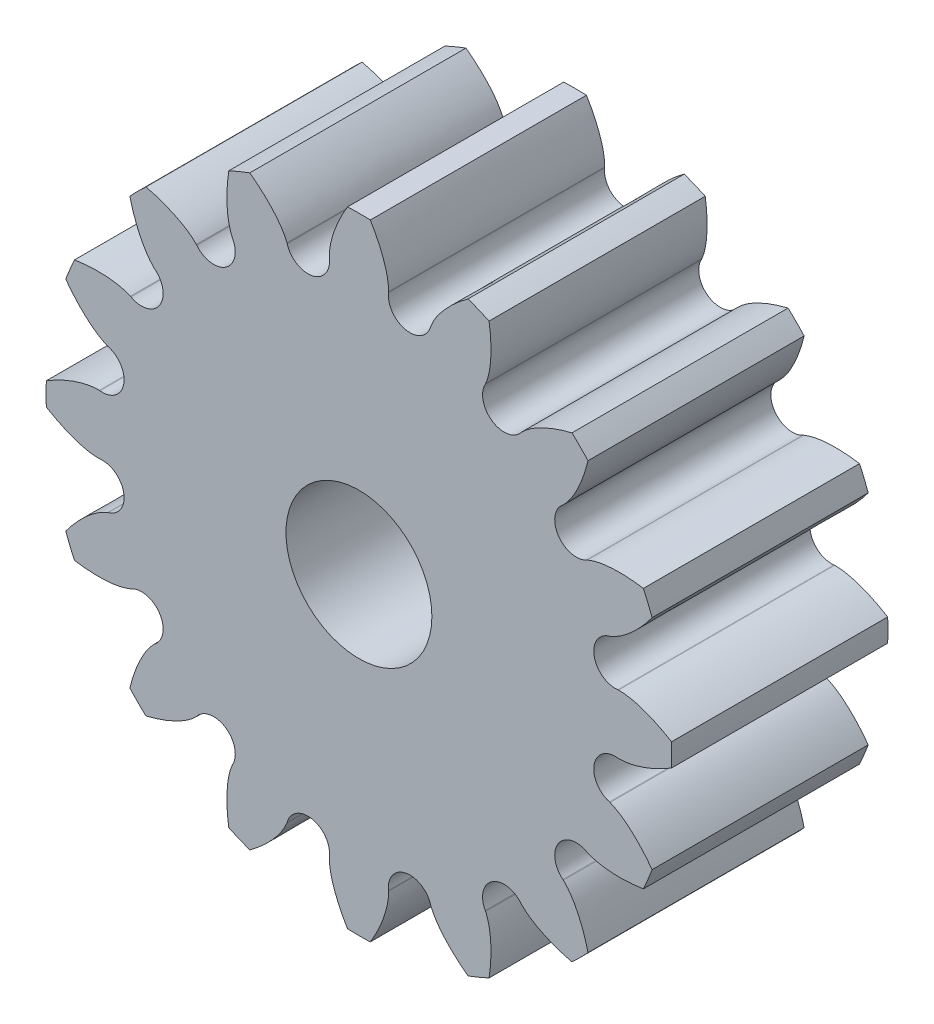
SolidWorks part; units mm, degrees
material "PE Low/Medium Density"
ref_plane "Front Plane" through (0, 0, 0) normal (0, 0, 1) x (1, 0, 0)
ref_plane "Top Plane" through (0, 0, 0) normal (0, 1, 0) x (1, 0, 0)
ref_plane "Right Plane" through (0, 0, 0) normal (1, 0, 0) x (0, 0, -1)
sketch "Involute construction sketch" plane through (0, 0, 0) normal (0, 0, 1) x (1, 0, 0)
  line L0 (0, 0) -> (-1.7946, 3.1652) construction
  line L1 (0, 0) -> (-1.096, 3.4696) construction
  line L2 (0, 0) -> (-0.3494, 3.6218) construction
  line L3 (0, 0) -> (0.4126, 3.6151) construction
  line L4 (-2.9284, 2.1595) -> (-2.4145, 2.722) construction
  line L5 (-2.4145, 2.722) -> (-1.7946, 3.1652) construction
  line L6 (-1.7946, 3.1652) -> (-1.096, 3.4696) construction
  line L7 (0, 0) -> (-2.4145, 2.722) construction
  line L8 (0, 0) -> (-2.9284, 2.1595) construction
  line L9 (-1.096, 3.4696) -> (-0.3494, 3.6218) construction
  line L10 (-0.3494, 3.6218) -> (0.4126, 3.6151) construction
  line L11 (-2.9284, 2.1595) -> (-0.6672, 5.2259) construction
  line L12 (-2.4145, 2.722) -> (-0.1342, 4.7446) construction
  line L13 (-1.7946, 3.1652) -> (0.194, 4.2927) construction
  line L14 (-1.096, 3.4696) -> (0.3572, 3.9286) construction
  line L15 (-0.3494, 3.6218) -> (0.4091, 3.6949) construction
  line L17 (0, 0) -> (0, 5.7859) construction
  line L18 (0, 0) -> (0.3795, 3.8534) construction
  line L19 (0, 0) -> (0.6516, 3.2759) construction
  circle A0 centre (0, 0) radius 3.3401 construction
  circle A1 centre (0, 0) radius 3.6386 construction
  circle A2 centre (0, 0) radius 3.8721 construction
  circle A3 centre (0, 0) radius 4.3561 construction
  spline S0 degree 3 poles (0.4126, 3.6151) (0.4138, 3.7219) (0.3608, 3.9584) (0.0805, 4.5656) (-0.328, 4.974) (-0.6672, 5.2259) knots 0 0 0 0 0.160058 0.360049 1 1 1 1 construction
  point P17 (0.1584, 4.3532)
  dimension "D1" = 6.6802
  dimension "D2" = 7.2771
  dimension "D3" = 7.7442
  dimension "D4" = 8.7122
  dimension "D5" = 0.762
  dimension "D6" = 1.524
  dimension "D7" = 2.286
  dimension "D8" = 3.048
  dimension "D9" = 3.81
  dimension "D10" = 5.625
  dimension "D11" = 11.25
sketch "Sketch2" plane through (0, 0, 0) normal (0, 0, 1) x (1, 0, 0)
  line L0 (0, 4.3561) -> (0, 3.3401)
  line L1 (0, 0) -> (0, 5.7859) construction
  line L2 (0.4126, 3.6151) -> (0.4114, 3.605)
  line L3 (0, 0) -> (0.4126, 3.6151) construction
  circle A0 centre (0, 0) radius 4.3561 construction
  circle A1 centre (0, 0) radius 3.3401 construction
  arc A2 (0, 4.3561) -> (0.1584, 4.3532) centre (0, 0) cw
  arc A3 (0, 3.3401) -> (0.6516, 3.2759) centre (0, 0) cw
  arc A4 (0.4114, 3.605) -> (0.6516, 3.2759) centre (0.7103, 3.5709) ccw
  spline S0 degree 3 poles (0.1584, 4.3532) (0.2397, 4.2197) (0.3556, 3.9815) (0.4138, 3.7219) (0.4126, 3.6151) knots 0 0 0 0 0.595051 1 1 1 1
sketch "Sketch3" plane through (0, 0, 0) normal (0, 0, 1) x (1, 0, 0)
  circle A0 centre (0, 0) radius 3.3401
  circle A1 centre (0, 0) radius 1.016
  dimension "D1" = 6.6802
  dimension "D2" = 2.032
extrude "Base" add sketch "Sketch3" along normal blind 3.0099
extrude "Half tooth" add sketch "Sketch2" along normal up to surface (3.0099 mm away) up to face at (3.3401, 0, 3.0099)
ref_plane "Midplane of half tooth" through (0, 0, 0) normal (-1, 0, 0) x (0, 0, 1)
mirror "Mirror of half tooth" about plane through (0, 0, 0) normal (-1, 0, 0) of "Half tooth"
pattern_circular "Pattern of tooth" count 16 over 360 of "Half tooth", "Mirror of half tooth"
equation "\"radtodeg\"= 180 / PI'radian to degree conversion [ ]"
equation "\"phi\"= 20'pressure angle [deg]"
equation "\"N\"= 16'number of teeth [teeth]"
equation "\"A\"= 0.343in'diameter of addendum circle [inch]"
equation "\"B\"= 0.263in'diameter of dedendum circle [inch]"
equation "\"P\"= ( \"N\" + 2 ) / \"A\"'diametral pitch [teeth/inch]"
equation "\"d\"= \"N\" / \"P\"'diameter of pitch circle [inch]"
equation "\"cp\"= PI / \"P\"'circular pitch [inch/teeth]"
equation "\"add\"= 1 / \"P\"'addendum [inch]"
equation "\"ded\"= - ( \"B\" - \"d\" ) / 2'dedendum [inch]"
equation "\"clear\"= \"ded\" - \"add\"'clearance [inch]"
equation "\"C\"= \"B\" + 2 * \"clear\"'diameter of clearance circle [inch]"
equation "\"h\"= \"add\" + \"ded\"'tooth height / whole depth [inch]"
equation "\"s\"= \"d\" * cos ( \"phi\" * 1 / \"radtodeg\" )'diameter of base circle [inch]"
equation "\"t\"= ( PI / 2 ) / \"P\"'tooth width at diameter of pitch circle diameter [inch]"
equation "\"alpha\"= ( \"t\" / ( \"d\" / 2 ) * \"radtodeg\" ) / 2'arc angle for half of tooth width at pitch circle diameter [inch]"
equation "\"bore\"= 0.0800'bore of hub [inch]"
equation "\"D4@Involute construction sketch\"= \"A\"'addendum circle"
equation "\"D3@Involute construction sketch\"= \"d\"'pitch circle"
equation "\"D2@Involute construction sketch\"= \"s\"'base circle"
equation "\"D1@Involute construction sketch\"= \"B\"'dedendum circle"
equation "\"seg\"= \"D5@Involute construction sketch\"'size of one involute segment [inch]"
equation "\"D6@Involute construction sketch\"=2*\"seg\""
equation "\"D7@Involute construction sketch\"=3*\"seg\""
equation "\"D8@Involute construction sketch\"=4*\"seg\""
equation "\"D9@Involute construction sketch\"=5*\"seg\""
equation "\"D10@Involute construction sketch\"=\"alpha\""
equation "\"D11@Involute construction sketch\"=2*\"alpha\""
equation "\"D1@Sketch3\"=\"B\""
equation "\"D1@CirPattern1\"=\"N\""
equation "\"D2@Sketch3\"=\"bore\""
equation "\"D1@Pattern of tooth\"=\"N\""
